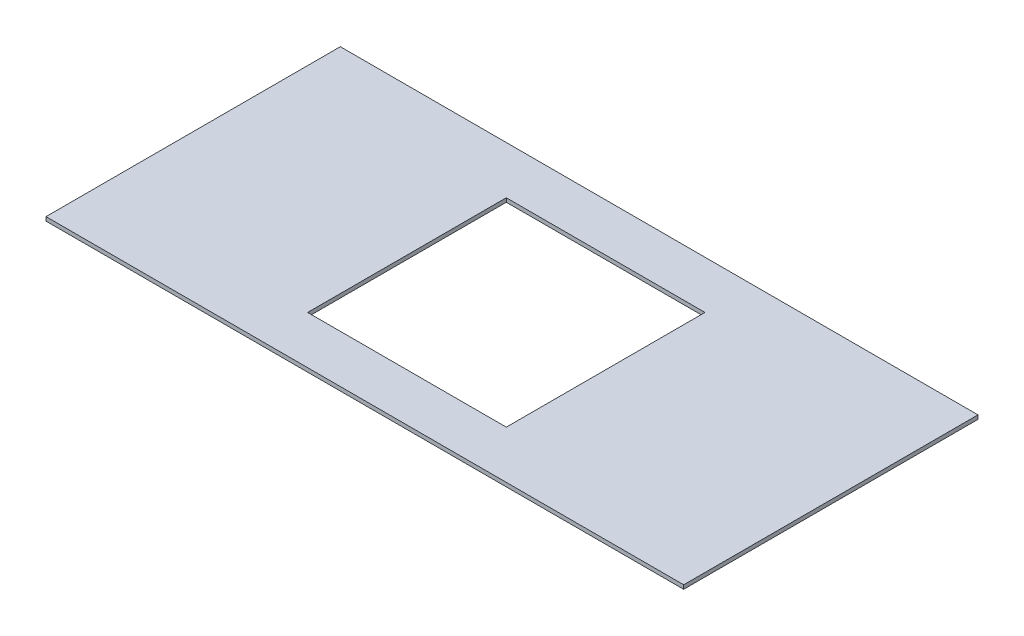
SolidWorks part; units mm, degrees
ref_plane "Front Plane" through (0, 0, 0) normal (0, 0, 1) x (1, 0, 0)
ref_plane "Top Plane" through (0, 0, 0) normal (0, 1, 0) x (1, 0, 0)
ref_plane "Right Plane" through (0, 0, 0) normal (1, 0, 0) x (0, 0, -1)
sketch "Sketch2" plane through (0, 0, 0) normal (0, 1, 0) x (1, 0, 0)
  line L1 (-65, 30) -> (65, 30)
  line L2 (-65, 30) -> (-65, -30)
  line L3 (-65, -30) -> (65, -30)
  line L4 (65, 30) -> (65, -30)
  line L5 (-65, 30) -> (65, -30) construction
  line L6 (-65, -30) -> (65, 30) construction
  point P0 (0, 0)
  dimension "D1" = 130
  dimension "D2" = 60
extrude "Boss-Extrude1" add sketch "Sketch2" along normal blind 0.8
sketch "Sketch3" plane through (0, 0, 0) normal (0, 1, 0) x (1, 0, 0)
  line L1 (-21.4136, 20.25) -> (19.0864, 20.25)
  line L2 (-21.4136, 20.25) -> (-21.4136, -20.25)
  line L3 (-21.4136, -20.25) -> (19.0864, -20.25)
  line L4 (19.0864, 20.25) -> (19.0864, -20.25)
  line L5 (-21.4136, 20.25) -> (19.0864, -20.25) construction
  line L6 (-21.4136, -20.25) -> (19.0864, 20.25) construction
  point P0 (-1.1636, 0)
  dimension "D1" = 40.5
  dimension "D2" = 40.5
extrude "Cut-Extrude1" cut sketch "Sketch3" along normal blind 3
